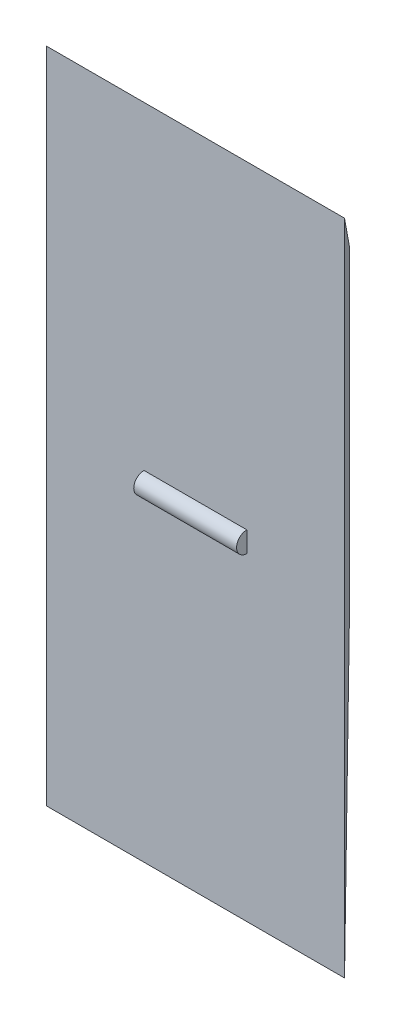
SolidWorks part; units mm, degrees
ref_plane "Plan de face" through (0, 0, 0) normal (0, 0, 1) x (1, 0, 0)
ref_plane "Plan de dessus" through (0, 0, 0) normal (0, 1, 0) x (1, 0, 0)
ref_plane "Plan de droite" through (0, 0, 0) normal (1, 0, 0) x (0, 0, -1)
sketch "Esquisse1" plane through (0, 0, 0) normal (0, 0, 1) x (1, 0, 0)
  line L1 (-14.5, 29.5) -> (14.5, 29.5)
  line L2 (-14.5, 29.5) -> (-14.5, -29.5)
  line L3 (-14.5, -29.5) -> (14.5, -29.5)
  line L4 (14.5, 29.5) -> (14.5, -29.5)
  line L5 (-14.5, 29.5) -> (14.5, -29.5) construction
  line L6 (-14.5, -29.5) -> (14.5, 29.5) construction
  point P0 (0, 0)
  dimension "D1" = 29
  dimension "D2" = 59
ref_plane "Plan1" through (0, 0, 30) normal (0, 0, 1) x (1, 0, 0)
sketch "Esquisse2" plane through (0, 0, 30) normal (0, 0, 1) x (1, 0, 0)
  line L0 (-14.5, -64) -> (-14.5, 64)
  line L1 (-14.5, -64) -> (43.5, -64)
  line L2 (-14.5, 64) -> (43.5, 64)
  line L3 (43.5, -64) -> (43.5, 64)
  line L4 (-14.5, 29.5) -> (-14.5, -29.5) construction
  line L5 (43.5, 64) -> (-14.5, -64) construction
  point P6 (-14.5, 0)
  point P7 (-14.5, 0)
  point P8 (14.5, 0)
  dimension "D1" = 58
  dimension "D2" = 128
loft "Lissage1" add profiles "Esquisse2", "Esquisse1"
ref_plane "Plan3" through (14.5, 0, 0) normal (1, 0, 0) x (0, 0, -1)
sketch "Esquisse4" plane through (14.5, 0, 0) normal (1, 0, 0) x (0, 0, -1)
  line L0 (-30, 31.9001) -> (-30, -31.9001) construction
  circle A0 centre (-30, 0) radius 2
extrude "Boss.-Extru.2" add sketch "Esquisse4" along normal blind 10 and the other way blind 10
